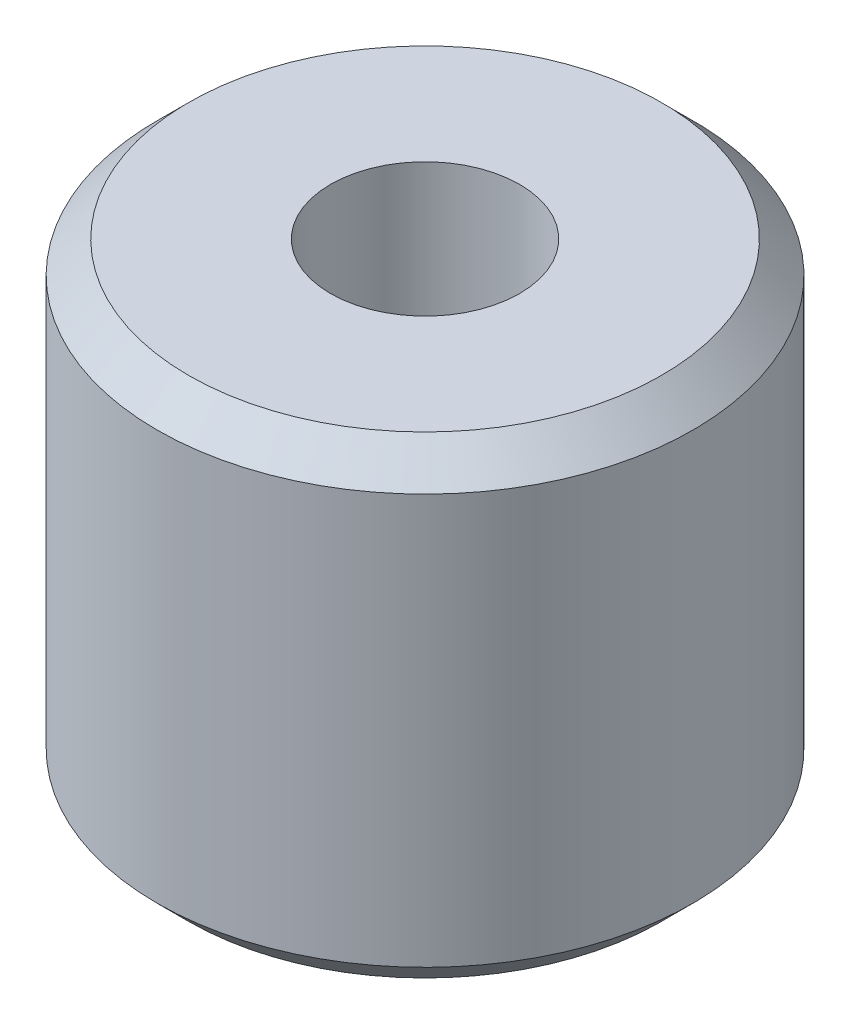
SolidWorks part; units mm, degrees
ref_plane "Front Plane" through (0, 0, 0) normal (0, 0, 1) x (1, 0, 0)
ref_plane "Top Plane" through (0, 0, 0) normal (0, 1, 0) x (1, 0, 0)
ref_plane "Right Plane" through (0, 0, 0) normal (1, 0, 0) x (0, 0, -1)
sketch "Sketch1" plane through (0, 0, 0) normal (0, 1, 0) x (1, 0, 0)
  circle A0 centre (0, 0) radius 3
  circle A1 centre (0, 0) radius 8.5
  dimension "D1" = 17
  dimension "D2" = 6
extrude "Boss-Extrude1" add sketch "Sketch1" along normal blind 15
chamfer "Chamfer1" distance 1 angle 45 2 edges at (0, 0, 8.5) (0, 15, 8.5)
